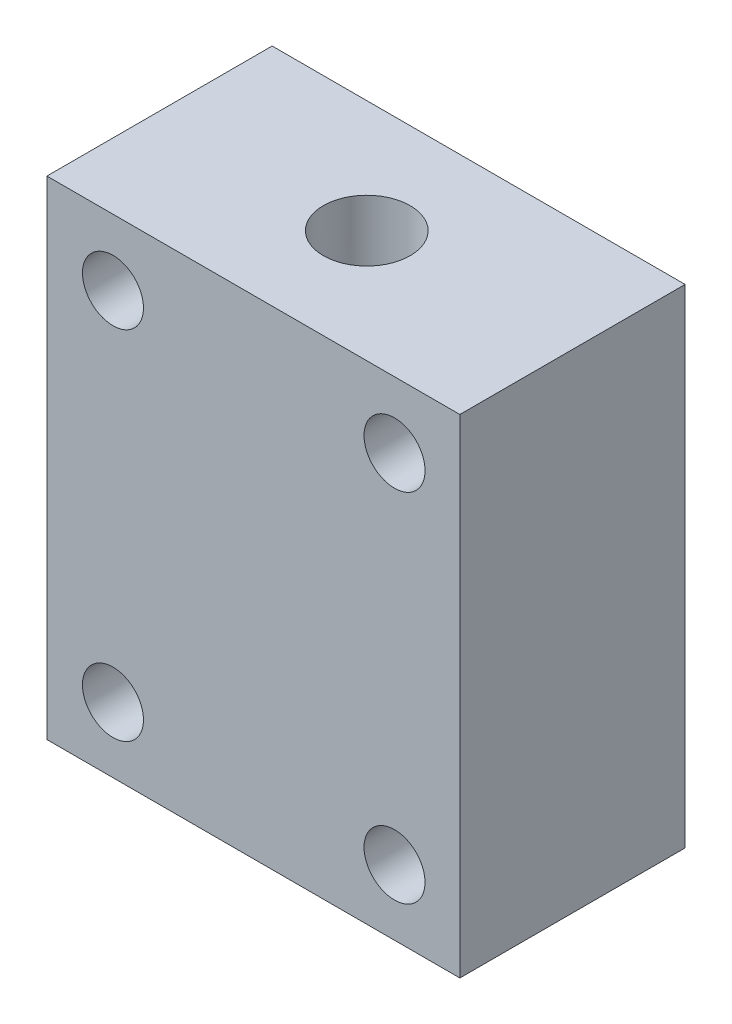
SolidWorks part; units mm, degrees
ref_plane "Front Plane" through (0, 0, 0) normal (1, 0, 0) x (0, 1, 0)
ref_plane "Top Plane" through (0, 0, 0) normal (0, 0, 1) x (0, 1, 0)
ref_plane "Right Plane" through (0, 0, 0) normal (0, 1, 0) x (-1, 0, 0)
sketch "Sketch1" plane through (0, 0, 0) normal (0, 0, 1) x (0, 1, 0)
  line L1 (-41.275, -34.925) -> (41.275, -34.925)
  line L2 (-41.275, -34.925) -> (-41.275, 34.925)
  line L3 (-41.275, 34.925) -> (41.275, 34.925)
  line L4 (41.275, -34.925) -> (41.275, 34.925)
  line L5 (-41.275, -34.925) -> (41.275, 34.925) construction
  line L6 (-41.275, 34.925) -> (41.275, -34.925) construction
  point P0 (0, 0)
  dimension "D1" = 41.275
  dimension "D2" = 34.925
extrude "Boss-Extrude1" add sketch "Sketch1" along normal mid plane 38.1
hole_wizard "3/8 Clearance Hole1" positions "Sketch3" profile "Sketch2" hole size "3/8" standard "ANSI Inch"
sketch "Sketch3" plane through (0, 0, -19.05) normal (0, 0, -1) x (-1, 0, 0)
  line L0 (-23.876, -30.226) -> (23.749, -30.226) construction
  line L1 (23.749, -30.226) -> (23.749, 30.099) construction
  line L2 (23.749, 30.099) -> (-23.876, 30.099) construction
  line L3 (-23.876, 30.099) -> (-23.876, -30.226) construction
  line L4 (-34.925, -41.275) -> (-34.925, 41.275) construction
  line L5 (-34.925, 41.275) -> (34.925, 41.275) construction
  point P0 (-23.876, -30.226)
  point P1 (-23.876, 30.099)
  point P3 (23.749, -30.226)
  point P5 (23.749, 30.099)
  dimension "D1" = 11.049
  dimension "D2" = 11.049
  dimension "D3" = 58.674
  dimension "D4" = 58.674
  dimension "D5" = 11.176
  dimension "D6" = 11.176
  dimension "D7" = 71.501
  dimension "D8" = 71.501
sketch "Sketch2" plane through (23.876, -30.226, -19.05) normal (1, 0, 0) x (0, 1, 0)
  line L0 (0, 0) -> (0, 41.2001)
  line L1 (0, 41.2001) -> (5.1594, 38.1)
  line L2 (5.1594, 38.1) -> (5.1594, 0)
  line L5 (5.1594, 0) -> (0, 0)
  line L10 (0, 41.2001) -> (-5.1594, 38.1) construction
  line L11 (0, -6.35) -> (0, 107.95) construction
  dimension "Hole Dia." = 10.3187
  dimension "Hole Depth" = 38.1
  dimension "Drill Angle" = 118
sketch "Sketch4" plane through (0, 0, 0) normal (0, 0, 1) x (0, 1, 0)
  circle A0 centre (-17.653, -0.127) radius 7.3422
  circle A1 centre (17.399, -0.127) radius 7.3422
  point P4 (0, 0)
  dimension "D1" = 14.6844
  dimension "D2" = 14.6844
  dimension "D3" = 35.052
  dimension "D4" = 17.653
  dimension "D5" = 0.127
  dimension "D6" = 0.127
extrude "Cut-Extrude2" cut sketch "Sketch4" along normal blind 28.448 from offset 19.05
sketch "Sketch5" plane through (0, 0, 0) normal (0, 0, 1) x (0, 1, 0)
  circle A0 centre (-17.653, -0.127) radius 12.7254
  circle A1 centre (17.399, -0.127) radius 12.7254
  point P4 (0, 0)
  dimension "D1" = 25.4508
  dimension "D2" = 25.4508
  dimension "D3" = 35.052
  dimension "D4" = 17.653
  dimension "D5" = 0.127
  dimension "D6" = 0.127
extrude "Cut-Extrude4" cut sketch "Sketch5" along normal blind 2.8194 from offset 19.05
sketch "Sketch6" plane through (0, 0, 0) normal (0, 1, 0) x (-1, 0, 0)
  circle A0 centre (-0.127, 0) radius 7.3422
  point P3 (-0.127, 0)
  dimension "D1" = 14.6844
extrude "Cut-Extrude6" cut sketch "Sketch6" against normal blind 60.452 from offset 41.275
